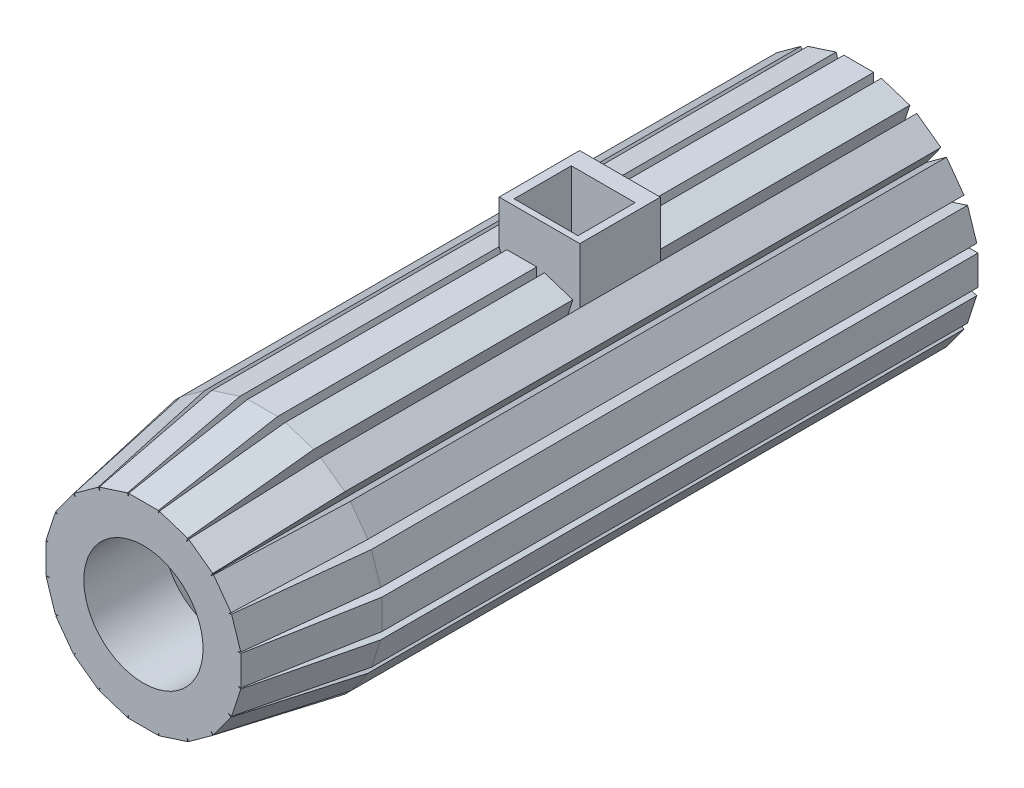
SolidWorks part; units mm, degrees
ref_plane "Front Plane" through (0, 0, 0) normal (0, 0, 1) x (1, 0, 0)
ref_plane "Top Plane" through (0, 0, 0) normal (0, 1, 0) x (1, 0, 0)
ref_plane "Right Plane" through (0, 0, 0) normal (1, 0, 0) x (0, 0, -1)
sketch "Sketch1" plane through (0, 0, 0) normal (0, 0, 1) x (1, 0, 0)
  circle A0 centre (0, 0) radius 1500
  dimension "D1" = 3000
extrude "Boss-Extrude1" add sketch "Sketch1" along normal blind 12000
chamfer "Chamfer1" distance 2000 angle 30 1 edges at (1500, 0, 12000)
shell "Shell1" thickness 100
ref_plane "Plane3" through (0, 2000, 0) normal (0, 1, 0) x (1, 0, 0)
sketch "Sketch4" plane through (0, 2000, 0) normal (0, 1, 0) x (1, 0, 0)
  line L0 (0, 0) -> (0, -12000) construction
  line L1 (-345.2995, -12000) -> (345.2995, -12000) construction
  line L2 (1400, 0) -> (-1400, 0) construction
  line L3 (-250, 0) -> (250, 0)
  line L4 (-250, 0) -> (-250, -12000)
  line L5 (-250, -12000) -> (250, -12000)
  line L6 (250, 0) -> (250, -12000)
  dimension "D1" = 250
  dimension "D2" = 500
extrude "Boss-Extrude4" add sketch "Sketch4" against normal up to next
sketch "Sketch6" plane through (-250, 0, 0) normal (-1, 0, 0) x (0, 0, 1)
  line L1 (0, 2000) -> (12000, 2000) construction
  line L2 (10000, 2000) -> (12000, 1634.8481)
  line L3 (12000, 238.1842) -> (12000, 2000) construction
  line L4 (12000, 1634.8481) -> (12000, 2000)
  line L5 (12000, 2000) -> (10000, 2000)
extrude "Cut-Extrude1" cut sketch "Sketch6" against normal through all both and the other way through all
pattern_circular "CirPattern2" count 20 over 360 about axis through (0, 0, 0) along (0, 0, 1) of "Cut-Extrude1", "Boss-Extrude4"
sketch "Sketch12" plane through (0, 0, 0) normal (0, 0, 1) x (1, 0, 0)
  circle A0 centre (0, 0) radius 1000
extrude "Cut-Extrude3" cut sketch "Sketch12" along normal up to surface (12000 mm away) up to face at (0, 0, 12000)
ref_plane "Plane5" through (0, 2700, 0) normal (0, 1, 0) x (1, 0, 0)
sketch "Sketch14" plane through (0, 2700, 0) normal (0, 1, 0) x (1, 0, 0)
  line L0 (-380.2699, -10000) -> (-380.2699, 0) construction
  line L1 (-380.2699, -4303.02) -> (973.3163, -4303.02)
  line L2 (-380.2699, -4303.02) -> (-380.2699, -5653.02)
  line L3 (-380.2699, -5653.02) -> (973.3163, -5653.02)
  line L4 (973.3163, -4303.02) -> (973.3163, -5653.02)
  line L5 (973.3163, 0) -> (973.3163, -10000) construction
  dimension "D1" = 1350
extrude "Boss-Extrude5" add sketch "Sketch14" along normal blind 0.008 and the other way up to next
sketch "Sketch16" plane through (0, 2700, 0) normal (0, 1, 0) x (1, 0, 0)
  line L1 (-228.3284, -4593.959) -> (843.1603, -4593.959)
  line L2 (-228.3284, -4593.959) -> (-228.3284, -5553.5012)
  line L3 (-228.3284, -5553.5012) -> (843.1603, -5553.5012)
  line L4 (843.1603, -4593.959) -> (843.1603, -5553.5012)
extrude "Cut-Extrude5" cut sketch "Sketch16" against normal up to next and the other way through all
